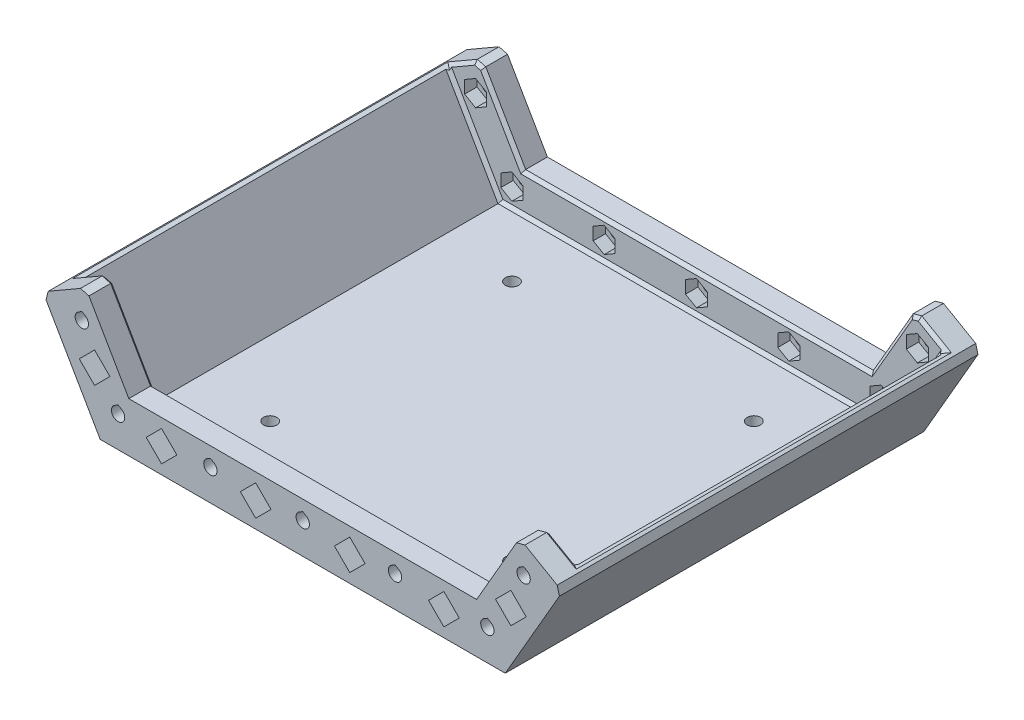
SolidWorks part; units mm, degrees
ref_plane "Front Plane" through (0, 0, 0) normal (0, 0, 1) x (1, 0, 0)
ref_plane "Top Plane" through (0, 0, 0) normal (0, 1, 0) x (1, 0, 0)
ref_plane "Right Plane" through (0, 0, 0) normal (1, 0, 0) x (0, 0, -1)
sketch "Sketch1" plane through (0, 0, 0) normal (0, 0, 1) x (1, 0, 0)
  line L0 (-83.8038, -32) -> (-65.3286, -64)
  line L2 (-65.3286, -64) -> (65.3286, -64) construction
  line L7 (-65.3286, -64) -> (65.3286, -64)
  line L8 (65.3286, -64) -> (83.8038, -32)
  line L9 (83.8038, -32) -> (80.3397, -30)
  line L10 (80.3397, -30) -> (63.0192, -60)
  line L11 (63.0192, -60) -> (-63.0192, -60)
  line L12 (-63.0192, -60) -> (-80.3397, -30)
  line L13 (-80.3397, -30) -> (-83.8038, -32)
  line L14 (0, -60) -> (0, -64) construction
  line L15 (-80.3397, -30) -> (80.3397, -30) construction
  line L16 (-80.3397, -30) -> (-73.4115, -26) construction
  line L17 (-89, -23) -> (-83.8038, -32) construction
  line L18 (-33, 57.1577) -> (-66, 0) construction
  line L19 (-66, 0) -> (-33, -57.1577) construction
  line L20 (-33, -57.1577) -> (33, -57.1577) construction
  line L21 (33, -57.1577) -> (66, 0) construction
  line L22 (66, 0) -> (33, 57.1577) construction
  line L23 (33, 57.1577) -> (-33, 57.1577) construction
  line L24 (-43, -23) -> (-89, -23) construction
  line L25 (-43, -23) -> (-43, 23) construction
  line L26 (-43, 23) -> (-89, 23) construction
  line L27 (-89, -23) -> (-89, 23) construction
  line L28 (-43, -23) -> (-89, 23) construction
  line L29 (-43, 23) -> (-89, -23) construction
  line L30 (43, -23) -> (89, -23) construction
  line L31 (43, -23) -> (43, 23) construction
  line L32 (43, 23) -> (89, 23) construction
  line L33 (89, -23) -> (89, 23) construction
  line L34 (43, -23) -> (89, 23) construction
  line L35 (43, 23) -> (89, -23) construction
  line L36 (89, -23) -> (83.8038, -32) construction
  circle A1 centre (0, 0) radius 57.1577 construction
  dimension "D1" = 132
  dimension "D2" = 4
  dimension "D3" = 32
  dimension "D4" = 12
  dimension "D5" = 46
  dimension "D6" = 64
extrude "Boss-Extrude1" add sketch "Sketch1" along normal mid plane 119
sketch "Sketch2" plane through (0, 0, 59.5) normal (0, 0, 1) x (1, 0, 0)
  line L0 (-83.8038, -32) -> (-69.9474, -24)
  line L1 (-69.9474, -24) -> (-56.091, -48)
  line L2 (-56.091, -48) -> (56.091, -48)
  line L3 (56.091, -48) -> (69.9474, -24)
  line L4 (69.9474, -24) -> (83.8038, -32)
  line L5 (83.8038, -32) -> (65.3286, -64)
  line L6 (65.3286, -64) -> (-65.3286, -64)
  line L7 (-65.3286, -64) -> (-83.8038, -32)
  line L8 (0, -48) -> (0, -64) construction
  dimension "D1" = 16
extrude "Boss-Extrude2" add sketch "Sketch2" along normal blind 8
sketch "Sketch3" plane through (0, 0, 59.5) normal (0, 0, -1) x (-1, 0, 0)
  line L0 (-75.1436, -27) -> (-67.3494, -40.5) construction
  line L1 (-80.3397, -30) -> (-69.9474, -24) construction
  line L2 (-67.3494, -40.5) -> (-59.5551, -54) construction
  line L3 (-59.5551, -54) -> (0, -54) construction
  line L4 (0, -54) -> (59.5551, -54) construction
  line L5 (59.5551, -54) -> (67.3494, -40.5) construction
  line L6 (67.3494, -40.5) -> (75.1436, -27) construction
  line L7 (69.9474, -24) -> (80.3397, -30) construction
  line L8 (-56.091, -48) -> (-63.0192, -60) construction
  circle A0 centre (-71.2465, -33.75) radius 2.15
  circle A1 centre (-59.5551, -54) radius 2.15
  circle A2 centre (-29.7776, -54) radius 2.15
  circle A3 centre (0, -54) radius 2.15
  circle A4 centre (29.7776, -54) radius 2.15
  circle A5 centre (59.5551, -54) radius 2.15
  circle A6 centre (71.2465, -33.75) radius 2.15
  dimension "D1" = 4.3
extrude "Cut-Extrude1" cut sketch "Sketch3" against normal through all
sketch "Sketch4" plane through (0, 0, 59.5) normal (0, 0, -1) x (-1, 0, 0)
  line L1 (-67.6965, -35.7996) -> (-67.6965, -31.7004)
  line L2 (-67.6965, -31.7004) -> (-71.2465, -29.6508)
  line L3 (-71.2465, -29.6508) -> (-74.7965, -31.7004)
  line L4 (-74.7965, -31.7004) -> (-74.7965, -35.7996)
  line L5 (-74.7965, -35.7996) -> (-71.2465, -37.8492)
  line L6 (-71.2465, -37.8492) -> (-67.6965, -35.7996)
  line L7 (-56.0051, -51.9504) -> (-59.5551, -49.9008)
  line L8 (-59.5551, -49.9008) -> (-63.1051, -51.9504)
  line L9 (-63.1051, -51.9504) -> (-63.1051, -56.0496)
  line L10 (-63.1051, -56.0496) -> (-59.5551, -58.0992)
  line L11 (-59.5551, -58.0992) -> (-56.0051, -56.0496)
  line L12 (-56.0051, -56.0496) -> (-56.0051, -51.9504)
  line L13 (-3.55, -56.0496) -> (0, -58.0992)
  line L14 (0, -58.0992) -> (3.55, -56.0496)
  line L15 (3.55, -56.0496) -> (3.55, -51.9504)
  line L16 (3.55, -51.9504) -> (0, -49.9008)
  line L17 (0, -49.9008) -> (-3.55, -51.9504)
  line L18 (-3.55, -51.9504) -> (-3.55, -56.0496)
  line L19 (56.0051, -56.0496) -> (59.5551, -58.0992)
  line L20 (59.5551, -58.0992) -> (63.1051, -56.0496)
  line L21 (63.1051, -56.0496) -> (63.1051, -51.9504)
  line L22 (63.1051, -51.9504) -> (59.5551, -49.9008)
  line L23 (59.5551, -49.9008) -> (56.0051, -51.9504)
  line L24 (56.0051, -51.9504) -> (56.0051, -56.0496)
  line L25 (67.6965, -31.7004) -> (67.6965, -35.7996)
  line L26 (67.6965, -35.7996) -> (71.2465, -37.8492)
  line L27 (71.2465, -37.8492) -> (74.7965, -35.7996)
  line L28 (74.7965, -35.7996) -> (74.7965, -31.7004)
  line L29 (74.7965, -31.7004) -> (71.2465, -29.6508)
  line L30 (71.2465, -29.6508) -> (67.6965, -31.7004)
  line L34 (-26.2276, -51.9504) -> (-29.7776, -49.9008)
  line L35 (-29.7776, -49.9008) -> (-33.3276, -51.9504)
  line L36 (-33.3276, -51.9504) -> (-33.3276, -56.0496)
  line L37 (-33.3276, -56.0496) -> (-29.7776, -58.0992)
  line L38 (-29.7776, -58.0992) -> (-26.2276, -56.0496)
  line L39 (-26.2276, -56.0496) -> (-26.2276, -51.9504)
  line L40 (33.3276, -51.9504) -> (29.7776, -49.9008)
  line L41 (29.7776, -49.9008) -> (26.2276, -51.9504)
  line L42 (26.2276, -51.9504) -> (26.2276, -56.0496)
  line L43 (26.2276, -56.0496) -> (29.7776, -58.0992)
  line L44 (29.7776, -58.0992) -> (33.3276, -56.0496)
  line L45 (33.3276, -56.0496) -> (33.3276, -51.9504)
  circle A0 centre (-71.2465, -33.75) radius 3.55 construction
  circle A1 centre (-59.5551, -54) radius 3.55 construction
  circle A2 centre (0, -54) radius 3.55 construction
  circle A3 centre (59.5551, -54) radius 3.55 construction
  circle A4 centre (71.2465, -33.75) radius 3.55 construction
  circle A5 centre (-29.7776, -54) radius 3.55 construction
  circle A6 centre (29.7776, -54) radius 3.55 construction
  dimension "D1" = 7.1
extrude "Cut-Extrude2" cut sketch "Sketch4" against normal blind 4
sketch "Sketch6" plane through (0, 0, 67.5) normal (0, 0, 1) x (1, 0, 0)
  line L0 (-69.9474, -24) -> (-83.8038, -32) construction
  line L1 (-76.8756, -28) -> (-67.1329, -44.875) construction
  line L2 (-67.1329, -44.875) -> (-60.7098, -56) construction
  line L3 (-60.7098, -56) -> (-30.3549, -56) construction
  line L4 (-30.3549, -56) -> (0, -56) construction
  line L5 (0, -56) -> (30.3549, -56) construction
  line L6 (30.3549, -56) -> (60.7098, -56) construction
  line L7 (60.7098, -56) -> (67.1329, -44.875) construction
  line L8 (67.1329, -44.875) -> (76.8756, -28) construction
  line L9 (83.8038, -32) -> (69.9474, -24) construction
  line L10 (0, -48) -> (0, -64) construction
  line L11 (56.091, -48) -> (-56.091, -48) construction
  line L12 (-65.3286, -64) -> (65.3286, -64) construction
  line L13 (-71.2465, -33.75) -> (-59.5551, -54) construction
  line L14 (-65.4008, -43.875) -> (-67.1329, -44.875) construction
  line L15 (71.2465, -33.75) -> (59.5551, -54) construction
  line L16 (65.4008, -43.875) -> (67.1329, -44.875) construction
  line L17 (-67.1329, -49.8247) -> (-72.0826, -44.875)
  line L18 (-67.1329, -49.8247) -> (-62.1831, -44.875)
  line L19 (-72.0826, -44.875) -> (-67.1329, -39.9253)
  line L20 (-62.1831, -44.875) -> (-67.1329, -39.9253)
  line L21 (-67.1329, -49.8247) -> (-67.1329, -39.9253) construction
  line L22 (-72.0826, -44.875) -> (-62.1831, -44.875) construction
  line L23 (62.1831, -44.875) -> (67.1329, -39.9253)
  line L24 (62.1831, -44.875) -> (67.1329, -49.8247)
  line L25 (67.1329, -39.9253) -> (72.0826, -44.875)
  line L26 (67.1329, -49.8247) -> (72.0826, -44.875)
  line L27 (62.1831, -44.875) -> (72.0826, -44.875) construction
  line L28 (67.1329, -39.9253) -> (67.1329, -49.8247) construction
  line L29 (50.4821, -56) -> (45.5324, -51.0503)
  line L30 (50.4821, -56) -> (45.5324, -60.9497)
  line L31 (45.5324, -51.0503) -> (40.5826, -56)
  line L32 (45.5324, -60.9497) -> (40.5826, -56)
  line L33 (50.4821, -56) -> (40.5826, -56) construction
  line L34 (45.5324, -51.0503) -> (45.5324, -60.9497) construction
  line L35 (-40.5826, -56) -> (-45.5324, -51.0503)
  line L36 (-40.5826, -56) -> (-45.5324, -60.9497)
  line L37 (-45.5324, -51.0503) -> (-50.4821, -56)
  line L38 (-45.5324, -60.9497) -> (-50.4821, -56)
  line L39 (-40.5826, -56) -> (-50.4821, -56) construction
  line L40 (-45.5324, -51.0503) -> (-45.5324, -60.9497) construction
  line L41 (-10.2277, -56) -> (-15.1775, -51.0503)
  line L42 (-10.2277, -56) -> (-15.1775, -60.9497)
  line L43 (-15.1775, -51.0503) -> (-20.1272, -56)
  line L44 (-15.1775, -60.9497) -> (-20.1272, -56)
  line L45 (-10.2277, -56) -> (-20.1272, -56) construction
  line L46 (-15.1775, -51.0503) -> (-15.1775, -60.9497) construction
  line L47 (20.1272, -56) -> (15.1775, -51.0503)
  line L48 (20.1272, -56) -> (15.1775, -60.9497)
  line L49 (15.1775, -51.0503) -> (10.2277, -56)
  line L50 (15.1775, -60.9497) -> (10.2277, -56)
  line L51 (20.1272, -56) -> (10.2277, -56) construction
  line L52 (15.1775, -51.0503) -> (15.1775, -60.9497) construction
  point P11 (0, -56)
  point P33 (45.5324, -56)
  point P34 (-45.5324, -56)
  point P43 (-15.1775, -56)
  point P48 (15.1775, -56)
  dimension "D1" = 7
extrude "Cut-Extrude3" cut sketch "Sketch6" against normal blind 5
mirror "Mirror1" about plane through (0, 0, 0) normal (0, 0, 1) of "Cut-Extrude3", "Boss-Extrude2", "Cut-Extrude1", "Cut-Extrude2"
chamfer "Chamfer1" distance 2 angle 45 6 edges at (-69.9474, -24, -63.5) (-69.9474, -24, 63.5) (-83.8038, -32, 0) (69.9474, -24, 63.5) (83.8038, -32, 0) (69.9474, -24, -63.5)
chamfer "Chamfer2" distance 1 angle 45 16 edges at (76.0096, -27.5, 59.5) (70.3135, -25.366, 59.5) (62.5192, -36.866, 59.5) (0, -48, 59.5) (-62.5192, -36.866, 59.5) (-70.3135, -25.366, 59.5) (-76.0096, -27.5, 59.5) (-80.3397, -30, 0) (-76.0096, -27.5, -59.5) (-70.3135, -25.366, -59.5) (-62.5192, -36.866, -59.5) (0, -48, -59.5) (62.5192, -36.866, -59.5) (70.3135, -25.366, -59.5) (76.0096, -27.5, -59.5) (80.3397, -30, 0)
sketch "Sketch7" plane through (0, -60, 0) normal (0, 1, 0) x (1, 0, 0)
  line L1 (39, -39) -> (-39, -39) construction
  line L2 (39, -39) -> (39, 39) construction
  line L3 (39, 39) -> (-39, 39) construction
  line L4 (-39, -39) -> (-39, 39) construction
  line L5 (39, -39) -> (-39, 39) construction
  line L6 (39, 39) -> (-39, -39) construction
  circle A0 centre (-39, 39) radius 2.15
  circle A1 centre (39, 39) radius 2.15
  circle A2 centre (39, -39) radius 2.15
  circle A3 centre (-39, -39) radius 2.15
  point P0 (0, 0)
  dimension "D3" = 4.3
  dimension "D1" = 78
  dimension "D2" = 78
extrude "Cut-Extrude4" cut sketch "Sketch7" against normal through all
chamfer "Chamfer3" distance 1 angle 45 6 edges at (-71.4295, -45.433, 59.5) (0, -60, 59.5) (71.4295, -45.433, 59.5) (71.4295, -45.433, -59.5) (0, -60, -59.5) (-71.4295, -45.433, -59.5)
sketch "Sketch9" plane through (0, 0, -67.5) normal (0, 0, -1) x (-1, 0, 0)
  line L0 (-72.3215, -31.888) -> (-71.2465, -31.2674)
  line L1 (-71.2465, -31.2674) -> (-70.1715, -31.888)
  line L2 (-70.1715, -31.888) -> (-72.3215, -31.888)
  line L3 (-71.2465, -31.2674) -> (-71.2465, -31.888) construction
  line L4 (-60.6301, -52.138) -> (-58.4801, -52.138)
  line L5 (-58.4801, -52.138) -> (-59.5551, -51.5174)
  line L6 (-59.5551, -51.5174) -> (-60.6301, -52.138)
  line L7 (-59.5551, -51.5174) -> (-59.5551, -52.138) construction
  line L8 (-28.7026, -52.138) -> (-30.8526, -52.138)
  line L9 (-30.8526, -52.138) -> (-29.7776, -51.5174)
  line L10 (-29.7776, -51.5174) -> (-28.7026, -52.138)
  circle A0 centre (-71.2465, -33.75) radius 2.15 construction
  circle A1 centre (-59.5551, -54) radius 2.15 construction
  circle A2 centre (-29.7776, -54) radius 2.15 construction
  dimension "D1" = 120
  dimension "D2" = 120
  dimension "D3" = 120
extrude "Cut-Extrude6" cut sketch "Sketch9" against normal through all
mirror "Mirror2" about plane through (0, 0, 0) normal (1, 0, 0) of "Cut-Extrude6"
sketch "Sketch10" plane through (0, 0, -67.5) normal (0, 0, -1) x (-1, 0, 0)
  line L0 (-1.075, -52.138) -> (1.075, -52.138)
  line L1 (1.075, -52.138) -> (0, -51.5174)
  line L2 (0, -51.5174) -> (-1.075, -52.138)
  circle A0 centre (0, -54) radius 2.15 construction
  dimension "D1" = 120
extrude "Cut-Extrude7" cut sketch "Sketch10" against normal through all
